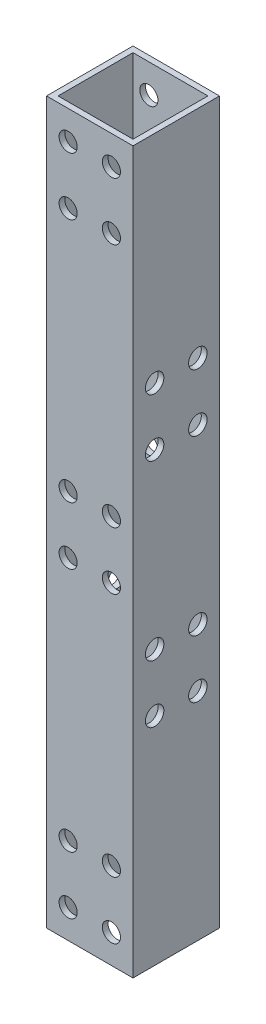
SolidWorks part; units mm, degrees
ref_plane "前视基准面" through (0, 0, 0) normal (0, 0, 1) x (1, 0, 0)
ref_plane "上视基准面" through (0, 0, 0) normal (0, 1, 0) x (1, 0, 0)
ref_plane "右视基准面" through (0, 0, 0) normal (1, 0, 0) x (0, 0, -1)
other "Configuration Table"
sketch "草图1" plane through (0, 0, 0) normal (0, 1, 0) x (1, 0, 0)
  line L1 (6.5, -6.5) -> (-6.5, -6.5)
  line L2 (6.5, -6.5) -> (6.5, 6.5)
  line L3 (6.5, 6.5) -> (-6.5, 6.5)
  line L4 (-6.5, -6.5) -> (-6.5, 6.5)
  line L5 (6.5, -6.5) -> (-6.5, 6.5) construction
  line L6 (6.5, 6.5) -> (-6.5, -6.5) construction
  line L7 (7.5, -7.5) -> (-7.5, -7.5)
  line L8 (7.5, -7.5) -> (7.5, 7.5)
  line L9 (7.5, 7.5) -> (-7.5, 7.5)
  line L10 (-7.5, -7.5) -> (-7.5, 7.5)
  line L11 (7.5, -7.5) -> (-7.5, 7.5) construction
  line L12 (7.5, 7.5) -> (-7.5, -7.5) construction
  point P0 (0, 0)
  point P6 (0, 0)
  dimension "D1" = 15
  dimension "D2" = 13
extrude "凸台-拉伸1" add sketch "草图1" along normal blind 125
sketch "草图2" plane through (0, 0, 7.5) normal (0, 0, 1) x (1, 0, 0)
  line L0 (0, 804.3358) -> (0, 762.8538) construction
  line L1 (-7.5, 62.5) -> (7.5, 62.5) construction
  line L2 (-7.5, 125) -> (-7.5, 0) construction
  line L3 (7.5, 125) -> (7.5, 0) construction
  line L4 (-7.5, 125) -> (7.5, 125) construction
  line L5 (-7.5, 115) -> (7.5, 115) construction
  line L6 (-7.5, 10) -> (7.5, 10) construction
  circle A0 centre (-3.75, 67.5) radius 1.575
  circle A1 centre (3.75, 67.5) radius 1.575
  circle A2 centre (-3.75, 57.5) radius 1.575
  circle A3 centre (3.75, 57.5) radius 1.575
  circle A4 centre (3.75, 120) radius 1.575
  circle A5 centre (-3.75, 120) radius 1.575
  circle A6 centre (-3.75, 110) radius 1.575
  circle A7 centre (3.75, 110) radius 1.575
  circle A8 centre (3.75, 15) radius 1.575
  circle A9 centre (-3.75, 15) radius 1.575
  circle A10 centre (-3.75, 5) radius 1.575
  circle A11 centre (3.75, 5) radius 1.575
  dimension "D2" = 3.15
  dimension "D5" = 3.15
  dimension "D8" = 3.75
  dimension "D1" = 62.5
  dimension "D3" = 7.5
  dimension "D4" = 10
  dimension "D6" = 5
  dimension "D7" = 10
extrude "切除-拉伸1" cut sketch "草图2" against normal up to surface (15 mm away) up to face at (0, 62.5, -7.5)
sketch "草图3" plane through (-7.5, 0, 0) normal (-1, 0, 0) x (0, 0, 1)
  line L0 (0, 809.7886) -> (0, 782.9032) construction
  line L1 (-7.5, 82.5) -> (7.5, 82.5) construction
  line L2 (-7.5, 125) -> (-7.5, 0) construction
  line L3 (7.5, 125) -> (7.5, 0) construction
  line L5 (7.5, 62.5) -> (-7.5, 62.5) construction
  line L6 (-7.5, 42.5) -> (7.5, 42.5) construction
  circle A0 centre (-3.75, 87.5) radius 1.6
  circle A1 centre (3.75, 87.5) radius 1.6
  circle A2 centre (-3.75, 77.5) radius 1.6
  circle A3 centre (3.75, 77.5) radius 1.6
  circle A68 centre (3.75, 47.5) radius 1.6
  circle A69 centre (-3.75, 47.5) radius 1.6
  circle A70 centre (3.75, 37.5) radius 1.6
  circle A71 centre (-3.75, 37.5) radius 1.6
  dimension "D2" = 3.2
  dimension "D1" = 20
  dimension "D3" = 7.5
  dimension "D4" = 10
extrude "切除-拉伸2" cut sketch "草图3" against normal up to surface (15 mm away) up to face at (7.5, 62.5, 0)
